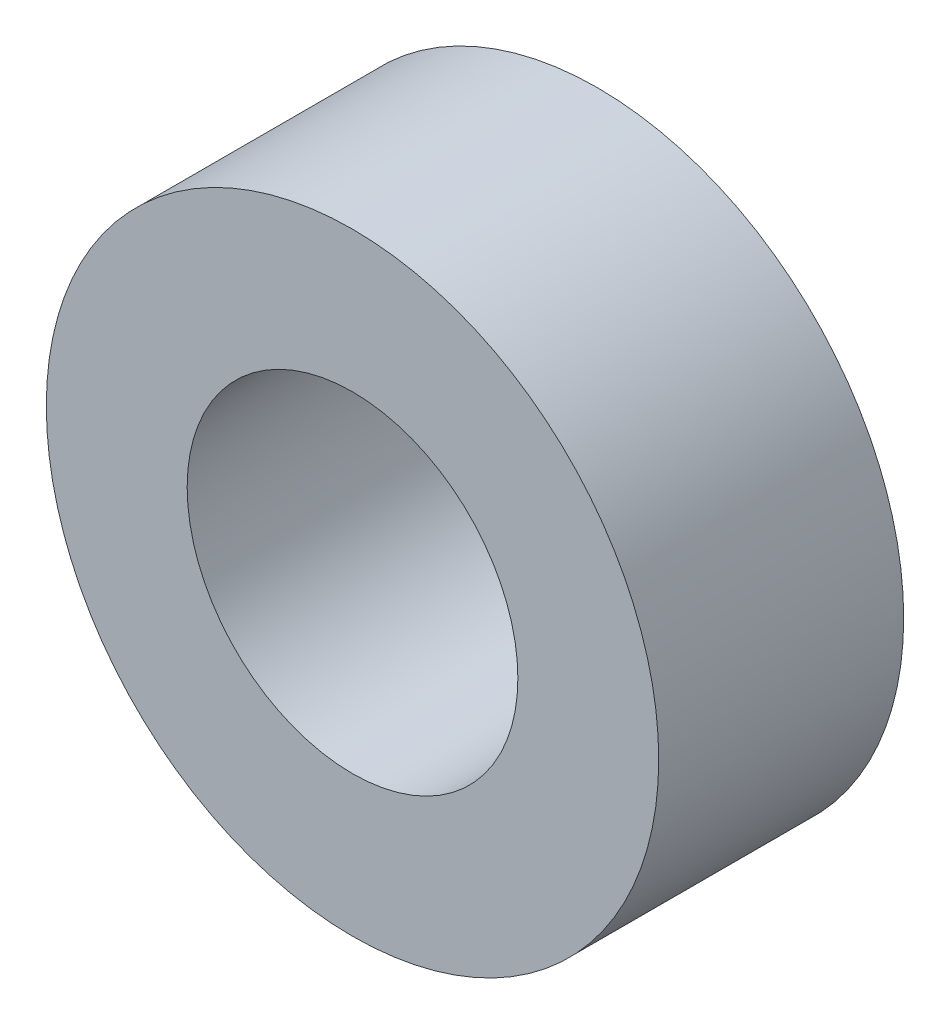
SolidWorks part; units mm, degrees
material "AISI 304"
ref_plane "正面" through (0, 0, 0) normal (0, 0, 1) x (1, 0, 0)
ref_plane "平面" through (0, 0, 0) normal (0, 1, 0) x (1, 0, 0)
ref_plane "右側面" through (0, 0, 0) normal (1, 0, 0) x (0, 0, -1)
sketch "ｽｹｯﾁ1" plane through (0, 0, 0) normal (0, 0, 1) x (1, 0, 0)
  circle A0 centre (0, 0) radius 2.5
  circle A1 centre (0, 0) radius 1.35
  dimension "D1" = 5
  dimension "D2" = 2.7
extrude "ﾎﾞｽ - 押し出し1" add sketch "ｽｹｯﾁ1" along normal blind 2
